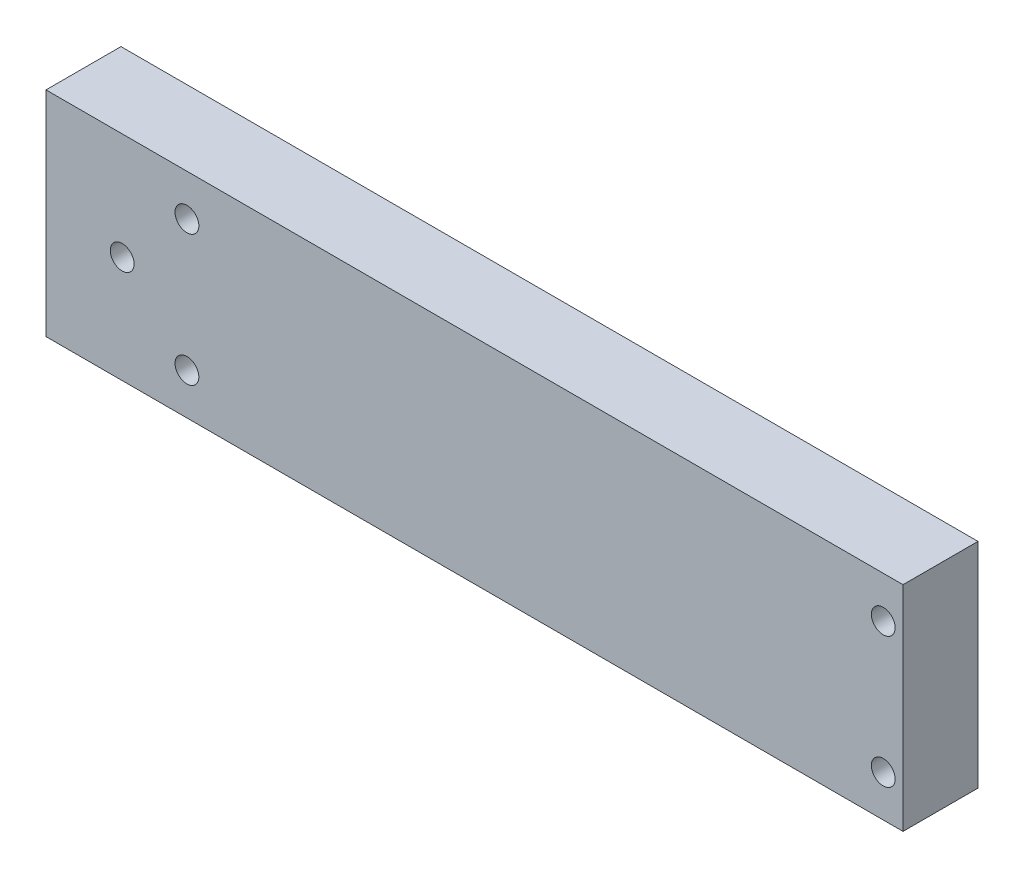
SolidWorks part; units mm, degrees
ref_plane "정면" through (0, 0, 0) normal (0, 0, 1) x (1, 0, 0)
ref_plane "윗면" through (0, 0, 0) normal (0, 1, 0) x (1, 0, 0)
ref_plane "우측면" through (0, 0, 0) normal (1, 0, 0) x (0, 0, -1)
sketch "스케치1" plane through (0, 0, 0) normal (0, 0, 1) x (1, 0, 0)
  line L1 (0, 0) -> (114.3, 0)
  line L2 (0, 0) -> (0, 28.5)
  line L3 (0, 28.5) -> (114.3, 28.5)
  line L4 (114.3, 0) -> (114.3, 28.5)
  dimension "D1" = 28.5
  dimension "D2" = 114.3
extrude "보스-돌출1" add sketch "스케치1" along normal blind 10
hole_wizard "구멍1" positions "스케치4" profile "스케치5" legacy end condition through all
sketch "스케치4" plane through (0, 0, 10) normal (0, 0, 1) x (1, 0, 0)
  line L0 (0, 28.5) -> (0, 0) construction
  line L1 (0, 14.25) -> (130.1055, 14.25) construction
  point P0 (18.796, 22.9813)
  point P4 (111.665, 22.9813)
  point P7 (10.16, 14.25)
  dimension "D1" = 10.16
  dimension "D2" = 8.636
  dimension "D3" = 92.869
  dimension "D4" = 17.4625
sketch "스케치5" plane through (18.796, 22.9813, 10) normal (1, 0, 0) x (0, -1, 0)
  line L0 (0, 0) -> (0, 10)
  line L1 (0, 10) -> (1.5875, 10)
  line L2 (1.5875, 10) -> (1.5875, 0)
  line L3 (1.5875, 0) -> (0, 0)
  line L4 (0, 110) -> (0, -10) construction
  dimension "지름" = 3.175
  dimension "깊이" = 10
ref_plane "평면1" through (0, 14.25, 0) normal (0, 1, 0) x (1, 0, 0)
mirror "대칭 복사1" about plane through (0, 14.25, 0) normal (0, 1, 0) of "구멍1"
